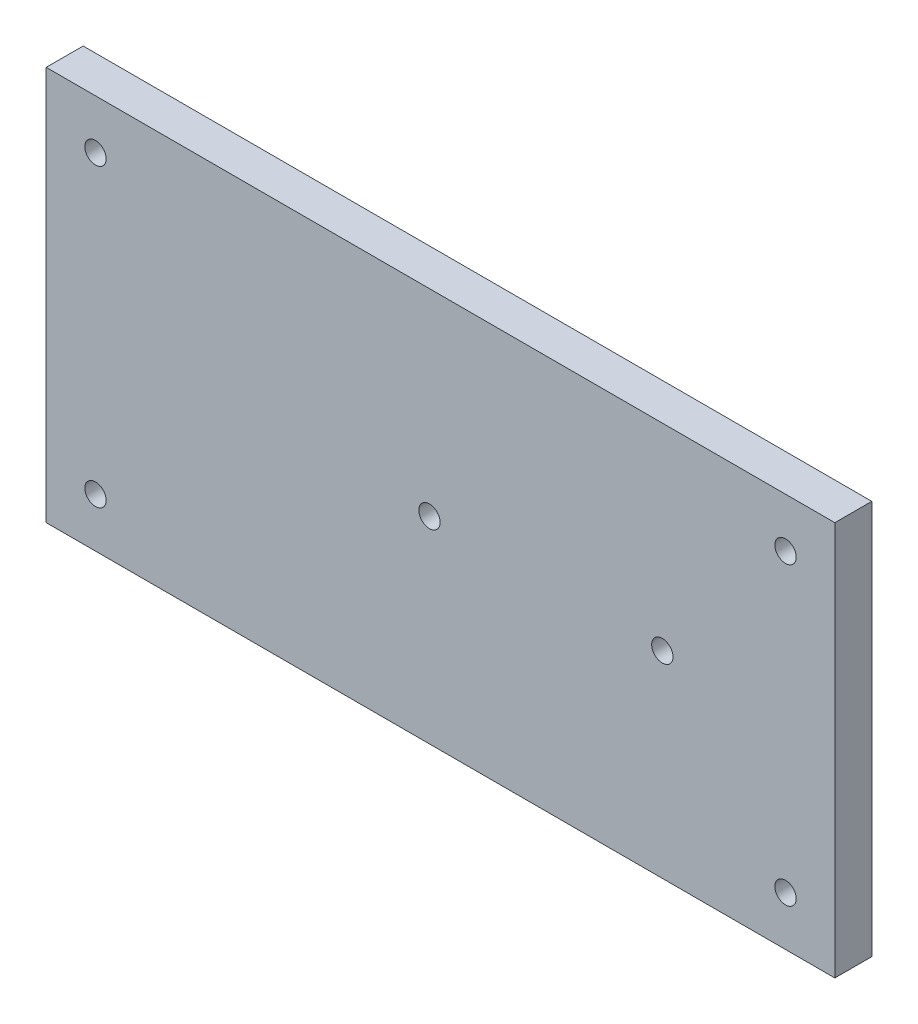
SolidWorks part; units mm, degrees
ref_plane "Front" through (0, 0, 0) normal (0, 0, 1) x (1, 0, 0)
ref_plane "Top" through (0, 0, 0) normal (0, 1, 0) x (1, 0, 0)
ref_plane "Right" through (0, 0, 0) normal (1, 0, 0) x (0, 0, -1)
sketch "Sketch1" plane through (0, 0, 0) normal (0, 0, 1) x (1, 0, 0)
  line L1 (0, 0) -> (203.2, 0)
  line L2 (0, 0) -> (0, 101.6)
  line L3 (0, 101.6) -> (203.2, 101.6)
  line L4 (203.2, 0) -> (203.2, 101.6)
  dimension "D1" = 101.6
  dimension "D2" = 203.2
extrude "Boss-Extrude1" add sketch "Sketch1" along normal blind 9.525
sketch "Sketch2" plane through (0, 0, 0) normal (1, 0, 0) x (0, 0, -1)
  line L0 (0, 0) -> (0, 101.6) construction
  line L1 (0, 76.2) -> (-1.5875, 76.2)
  line L2 (0, 76.2) -> (0, 25.4)
  line L3 (0, 25.4) -> (-1.5875, 25.4)
  line L4 (-1.5875, 76.2) -> (-1.5875, 25.4)
  line L5 (-9.525, 101.6) -> (0, 101.6) construction
  dimension "D1" = 25.4
  dimension "D2" = 50.8
  dimension "D3" = 1.5875
extrude "Cut-Extrude1" cut sketch "Sketch2" along normal blind 93.98 and the other way through all
hole_wizard "CBORE for M5 SBHCS1" positions "Sketch3" profile "Sketch4" counterbore size "M5" standard "ANSI Metric" end condition through all
sketch "Sketch3" plane through (0, 0, 0) normal (0, 0, -1) x (-1, 0, 0)
  line L0 (-203.2, 101.6) -> (0, 101.6) construction
  line L1 (0, 0) -> (-203.2, 0) construction
  line L2 (0, 101.6) -> (0, 76.2) construction
  line L3 (0, 25.4) -> (0, 0) construction
  line L4 (-203.2, 0) -> (-203.2, 101.6) construction
  point P0 (-190.5, 88.9)
  point P2 (-12.7, 88.9)
  point P4 (-12.7, 12.7)
  point P6 (-190.5, 12.7)
  dimension "D1" = 12.7
  dimension "D2" = 12.7
  dimension "D3" = 12.7
  dimension "D4" = 12.7
  dimension "D5" = 12.7
  dimension "D6" = 12.7
  dimension "D7" = 12.7
  dimension "D8" = 12.7
sketch "Sketch4" plane through (190.5, 88.9, 0) normal (1, 0, 0) x (0, 1, 0)
  line L0 (0, 0) -> (0, 9.525)
  line L1 (0, 9.525) -> (2.75, 9.525)
  line L3 (2.75, 9.525) -> (2.75, 2.75)
  line L4 (2.75, 2.75) -> (5.25, 2.75)
  line L5 (5.25, 2.75) -> (5.25, 0)
  line L7 (5.25, 0) -> (0, 0)
  line L11 (0, -6.35) -> (0, 107.95) construction
  dimension "Thru Hole Dia." = 5.5
  dimension "Thru Hole Depth" = 9.525
  dimension "C'Bore Dia." = 10.5
  dimension "C'Bore Depth" = 2.75
hole_wizard "M5 Clearance Hole1" positions "Sketch5" profile "Sketch6" hole size "M5" standard "ANSI Metric" end condition through all
sketch "Sketch5" plane through (0, 0, 9.525) normal (0, 0, 1) x (1, 0, 0)
  line L0 (203.2, 101.6) -> (0, 101.6) construction
  line L1 (203.2, 0) -> (203.2, 101.6) construction
  point P0 (158.75, 50.8)
  point P7 (98.7552, 50.8)
  dimension "D1" = 50.8
  dimension "D2" = 44.45
  dimension "D3" = 59.9948
sketch "Sketch6" plane through (158.75, 50.8, 9.525) normal (1, 0, 0) x (0, -1, 0)
  line L0 (0, 0) -> (0, 9.525)
  line L1 (0, 9.525) -> (2.75, 9.525)
  line L2 (2.75, 9.525) -> (2.75, 0)
  line L5 (2.75, 0) -> (0, 0)
  line L11 (0, -6.35) -> (0, 107.95) construction
  dimension "Thru Hole Dia." = 5.5
  dimension "Thru Hole Depth" = 9.525
